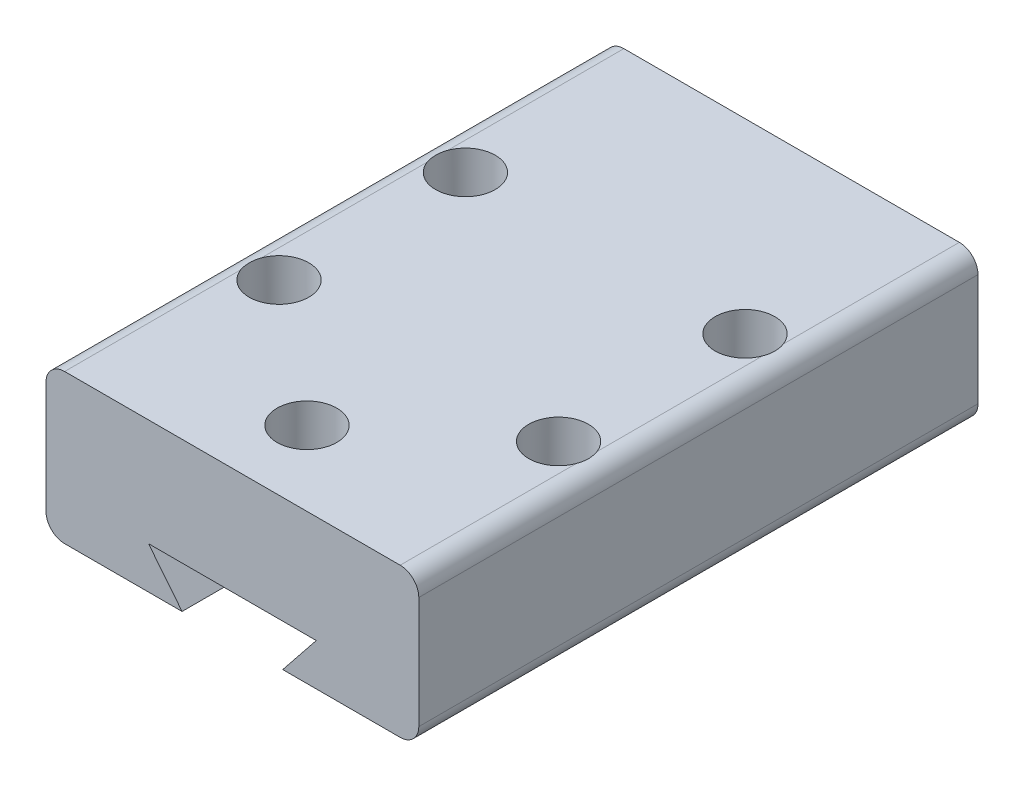
SolidWorks part; units mm, degrees
ref_plane "前视基准面" through (0, 0, 0) normal (0, 0, 1) x (1, 0, 0)
ref_plane "上视基准面" through (0, 0, 0) normal (0, 1, 0) x (1, 0, 0)
ref_plane "右视基准面" through (0, 0, 0) normal (1, 0, 0) x (0, 0, -1)
sketch "草图1" plane through (0, 0, 0) normal (0, 0, 1) x (1, 0, 0)
  line L0 (-34.1848, 24.7429) -> (-14.1848, 24.7429)
  line L1 (-14.1848, 24.7429) -> (-14.1848, 16.7429)
  line L2 (-14.1848, 16.7429) -> (-21.4848, 16.7429)
  line L3 (-21.4848, 16.7429) -> (-19.6848, 18.9929)
  line L4 (-19.6848, 18.9929) -> (-28.6848, 18.9929)
  line L5 (-28.6848, 18.9929) -> (-26.8848, 16.7429)
  line L6 (-26.8848, 16.7429) -> (-34.1848, 16.7429)
  line L7 (-34.1848, 16.7429) -> (-34.1848, 24.7429)
  dimension "D1" = 20
  dimension "D2" = 8
  dimension "D3" = 2.25
  dimension "D4" = 7.3
  dimension "D5" = 8
  dimension "D6" = 9
  dimension "D7" = 5.5
  dimension "D8" = 5.4
extrude "凸台-拉伸1" add sketch "草图1" along normal blind 30
fillet "圆角1" radius 1 4 edges at (-14.1848, 16.7429, 15) (-14.1848, 24.7429, 15) (-34.1848, 16.7429, 15) (-34.1848, 24.7429, 15)
sketch "草图3" plane through (0, 24.7429, 0) normal (0, 1, 0) x (1, 0, 0)
  line L1 (-15.1848, 0) -> (-33.1848, 0) construction
  line L3 (-15.1848, -30) -> (-33.1848, -30) construction
  line L4 (-24.1848, -30) -> (-24.1848, 0) construction
  line L5 (-33.1848, -15) -> (-15.1848, -15) construction
  line L6 (-33.1848, 0) -> (-33.1848, -30) construction
  line L7 (-15.1848, -30) -> (-15.1848, 0) construction
  circle A0 centre (-31.6848, -10) radius 1.6
  circle A1 centre (-31.6848, -20) radius 1.6
  circle A2 centre (-16.6848, -10) radius 1.6
  circle A3 centre (-16.6848, -20) radius 1.6
  circle A4 centre (-24.1848, -26) radius 1.6
  dimension "D1" = 3.2
  dimension "D2" = 3.2
  dimension "D3" = 3.2
  dimension "D4" = 3.2
  dimension "D5" = 15
  dimension "D6" = 10
  dimension "D7" = 10
  dimension "D8" = 7.5
  dimension "D9" = 15
  dimension "D10" = 10
  dimension "D11" = 7.5
  dimension "D12" = 10
  dimension "D13" = 3.2
  dimension "D14" = 4
extrude "切除-拉伸1" cut sketch "草图3" against normal blind 4
